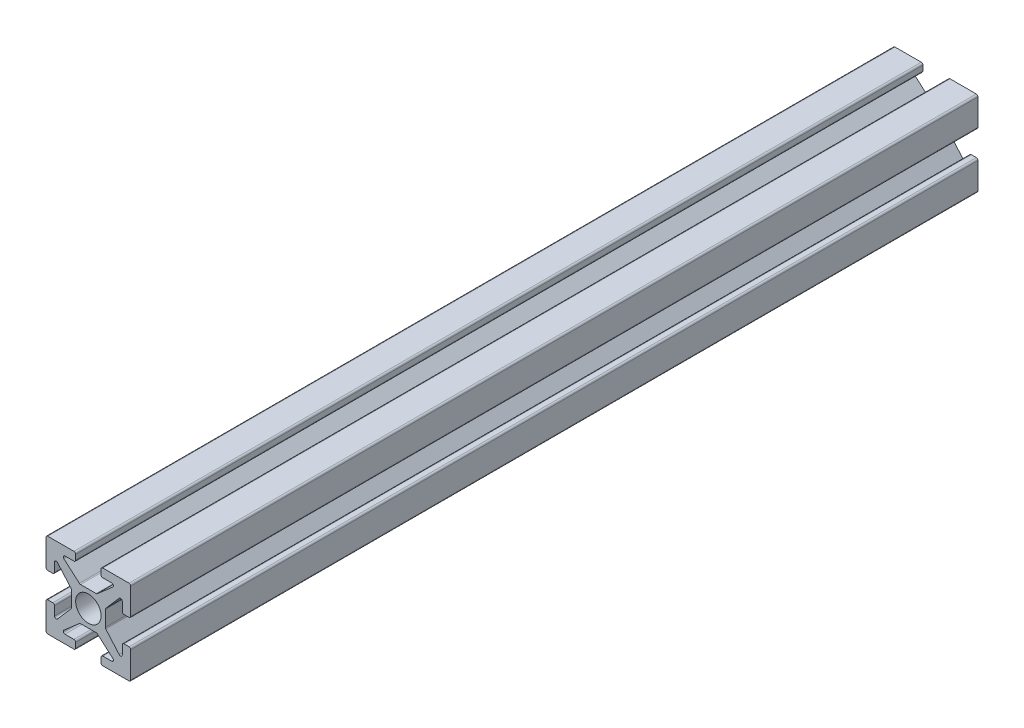
SolidWorks part; units mm, degrees
ref_plane "Front Plane" through (0, 0, 0) normal (0, 0, 1) x (1, 0, 0)
ref_plane "Top Plane" through (0, 0, 0) normal (0, 1, 0) x (1, 0, 0)
ref_plane "Right Plane" through (0, 0, 0) normal (1, 0, 0) x (0, 0, -1)
sketch "Model" plane through (0, 0, 0) normal (0, 0, 1) x (1, 0, 0)
  line L54 (1314.7405, 1308.4707) -> (1314.7405, 1305.3707)
  line L55 (1311.7898, 1309.1142) -> (1313.3898, 1307.2799)
  line L56 (1311.4405, 1306.1707) -> (1312.4998, 1306.1707)
  line L57 (1311.2405, 1305.3707) -> (1311.2405, 1305.9707)
  line L58 (1313.9405, 1308.6707) -> (1314.5405, 1308.6707)
  line L59 (1312.6313, 1306.5214) -> (1310.797, 1308.1214)
  line L60 (1313.7405, 1307.4113) -> (1313.7405, 1308.4707)
  line L61 (1314.5405, 1305.1707) -> (1311.4405, 1305.1707)
  line L62 (1308.0405, 1305.1707) -> (1304.9405, 1305.1707)
  line L63 (1308.684, 1308.1214) -> (1306.8497, 1306.5214)
  line L64 (1305.7405, 1308.4707) -> (1305.7405, 1307.4113)
  line L65 (1304.9405, 1308.6707) -> (1305.5405, 1308.6707)
  line L66 (1308.2405, 1305.9707) -> (1308.2405, 1305.3707)
  line L67 (1310.6655, 1308.1707) -> (1308.8155, 1308.1707)
  line L68 (1306.0912, 1307.2799) -> (1307.6912, 1309.1142)
  line L69 (1306.9812, 1306.1707) -> (1308.0405, 1306.1707)
  line L70 (1304.7405, 1305.3707) -> (1304.7405, 1308.4707)
  line L71 (1304.7405, 1311.8707) -> (1304.7405, 1314.9707)
  line L72 (1307.6912, 1311.2272) -> (1306.0912, 1313.0615)
  line L73 (1308.0405, 1314.1707) -> (1306.9812, 1314.1707)
  line L74 (1308.2405, 1314.9707) -> (1308.2405, 1314.3707)
  line L75 (1305.5405, 1311.6707) -> (1304.9405, 1311.6707)
  line L76 (1307.7405, 1309.2456) -> (1307.7405, 1311.0957)
  line L77 (1306.8497, 1313.8199) -> (1308.684, 1312.2199)
  line L78 (1305.7405, 1312.93) -> (1305.7405, 1311.8707)
  line L79 (1304.9405, 1315.1707) -> (1308.0405, 1315.1707)
  line L80 (1311.4405, 1315.1707) -> (1314.5405, 1315.1707)
  line L81 (1310.797, 1312.2199) -> (1312.6313, 1313.8199)
  line L82 (1313.7405, 1311.8707) -> (1313.7405, 1312.93)
  line L83 (1314.5405, 1311.6707) -> (1313.9405, 1311.6707)
  line L84 (1311.2405, 1314.3707) -> (1311.2405, 1314.9707)
  line L85 (1308.8155, 1312.1707) -> (1310.6655, 1312.1707)
  line L86 (1313.3898, 1313.0615) -> (1311.7898, 1311.2272)
  line L87 (1312.4998, 1314.1707) -> (1311.4405, 1314.1707)
  line L88 (1314.7405, 1314.9707) -> (1314.7405, 1311.8707)
  line L89 (1311.7405, 1311.0957) -> (1311.7405, 1309.2456)
  arc A1 (1314.5405, 1305.1707) -> (1314.7405, 1305.3707) centre (1314.5405, 1305.3707) ccw
  arc A2 (1313.3898, 1307.2799) -> (1313.7405, 1307.4113) centre (1313.5405, 1307.4113) ccw
  arc A3 (1312.4998, 1306.1707) -> (1312.6313, 1306.5214) centre (1312.4998, 1306.3707) ccw
  arc A4 (1311.2405, 1305.3707) -> (1311.4405, 1305.1707) centre (1311.4405, 1305.3707) ccw
  arc A5 (1311.4405, 1306.1707) -> (1311.2405, 1305.9707) centre (1311.4405, 1305.9707) ccw
  arc A6 (1314.7405, 1308.4707) -> (1314.5405, 1308.6707) centre (1314.5405, 1308.4707) ccw
  arc A7 (1313.9405, 1308.6707) -> (1313.7405, 1308.4707) centre (1313.9405, 1308.4707) ccw
  arc A8 (1311.7405, 1309.2456) -> (1311.7898, 1309.1142) centre (1311.9405, 1309.2456) ccw
  arc A9 (1310.797, 1308.1214) -> (1310.6655, 1308.1707) centre (1310.6655, 1307.9707) ccw
  arc A10 (1304.7405, 1305.3707) -> (1304.9405, 1305.1707) centre (1304.9405, 1305.3707) ccw
  arc A11 (1306.8497, 1306.5214) -> (1306.9812, 1306.1707) centre (1306.9812, 1306.3707) ccw
  arc A12 (1305.7405, 1307.4113) -> (1306.0912, 1307.2799) centre (1305.9405, 1307.4113) ccw
  arc A13 (1304.9405, 1308.6707) -> (1304.7405, 1308.4707) centre (1304.9405, 1308.4707) ccw
  arc A14 (1305.7405, 1308.4707) -> (1305.5405, 1308.6707) centre (1305.5405, 1308.4707) ccw
  arc A15 (1308.0405, 1305.1707) -> (1308.2405, 1305.3707) centre (1308.0405, 1305.3707) ccw
  arc A16 (1308.2405, 1305.9707) -> (1308.0405, 1306.1707) centre (1308.0405, 1305.9707) ccw
  arc A17 (1308.8155, 1308.1707) -> (1308.684, 1308.1214) centre (1308.8155, 1307.9707) ccw
  arc A18 (1307.6912, 1309.1142) -> (1307.7405, 1309.2456) centre (1307.5405, 1309.2456) ccw
  arc A19 (1304.9405, 1315.1707) -> (1304.7405, 1314.9707) centre (1304.9405, 1314.9707) ccw
  arc A20 (1306.0912, 1313.0615) -> (1305.7405, 1312.93) centre (1305.9405, 1312.93) ccw
  arc A21 (1306.9812, 1314.1707) -> (1306.8497, 1313.8199) centre (1306.9812, 1313.9707) ccw
  arc A22 (1308.2405, 1314.9707) -> (1308.0405, 1315.1707) centre (1308.0405, 1314.9707) ccw
  arc A23 (1308.0405, 1314.1707) -> (1308.2405, 1314.3707) centre (1308.0405, 1314.3707) ccw
  arc A24 (1304.7405, 1311.8707) -> (1304.9405, 1311.6707) centre (1304.9405, 1311.8707) ccw
  arc A25 (1305.5405, 1311.6707) -> (1305.7405, 1311.8707) centre (1305.5405, 1311.8707) ccw
  arc A26 (1307.7405, 1311.0957) -> (1307.6912, 1311.2272) centre (1307.5405, 1311.0957) ccw
  arc A27 (1308.684, 1312.2199) -> (1308.8155, 1312.1707) centre (1308.8155, 1312.3707) ccw
  arc A28 (1314.7405, 1314.9707) -> (1314.5405, 1315.1707) centre (1314.5405, 1314.9707) ccw
  arc A29 (1312.6313, 1313.8199) -> (1312.4998, 1314.1707) centre (1312.4998, 1313.9707) ccw
  arc A30 (1313.7405, 1312.93) -> (1313.3898, 1313.0615) centre (1313.5405, 1312.93) ccw
  arc A31 (1314.5405, 1311.6707) -> (1314.7405, 1311.8707) centre (1314.5405, 1311.8707) ccw
  arc A32 (1313.7405, 1311.8707) -> (1313.9405, 1311.6707) centre (1313.9405, 1311.8707) ccw
  arc A33 (1311.4405, 1315.1707) -> (1311.2405, 1314.9707) centre (1311.4405, 1314.9707) ccw
  arc A34 (1311.2405, 1314.3707) -> (1311.4405, 1314.1707) centre (1311.4405, 1314.3707) ccw
  arc A35 (1310.6655, 1312.1707) -> (1310.797, 1312.2199) centre (1310.6655, 1312.3707) ccw
  arc A36 (1311.7898, 1311.2272) -> (1311.7405, 1311.0957) centre (1311.9405, 1311.0957) ccw
  circle A37 centre (1309.7405, 1310.1707) radius 1.5
  dimension "D3" = 3
  dimension "D1" = 10
  dimension "D2" = 3
extrude "Boss-Extrude1" add sketch "Model" along normal blind 100
